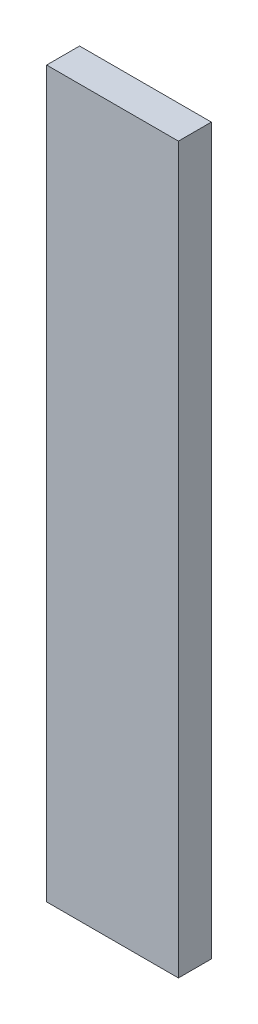
SolidWorks part; units mm, degrees
ref_plane "Front Plane" through (0, 0, 0) normal (0, 0, 1) x (1, 0, 0)
ref_plane "Top Plane" through (0, 0, 0) normal (0, 1, 0) x (1, 0, 0)
ref_plane "Right Plane" through (0, 0, 0) normal (1, 0, 0) x (0, 0, -1)
sketch "Sketch1" plane through (0, 0, 0) normal (0, 0, 1) x (1, 0, 0)
  line L1 (0, 0) -> (50.8, 0)
  line L2 (0, 0) -> (0, 279.4)
  line L3 (0, 279.4) -> (50.8, 279.4)
  line L4 (50.8, 0) -> (50.8, 279.4)
  dimension "D1" = 279.4
  dimension "D2" = 50.8
extrude "Boss-Extrude1" add sketch "Sketch1" along normal blind 12.7
